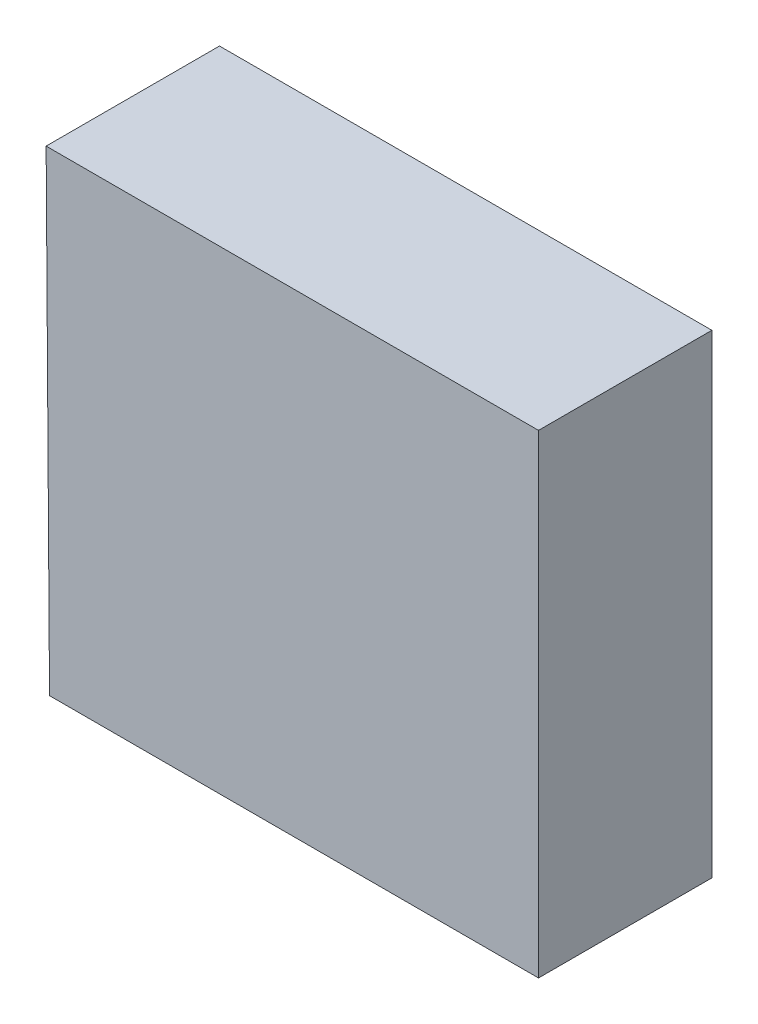
SolidWorks part; units mm, degrees
ref_plane "Front Plane" through (0, 0, 0) normal (0, 0, 1) x (1, 0, 0)
ref_plane "Top Plane" through (0, 0, 0) normal (0, 1, 0) x (1, 0, 0)
ref_plane "Right Plane" through (0, 0, 0) normal (1, 0, 0) x (0, 0, -1)
sketch "Sketch1" plane through (0, 0, 0) normal (0, 0, 1) x (1, 0, 0)
  line L0 (8.1788, 5.3086) -> (8.1788, -5.334)
  line L1 (8.1788, -5.334) -> (-2.794, -5.334)
  line L2 (-2.794, -5.334) -> (-2.8702, 5.3086)
  line L3 (-2.8702, 5.3086) -> (8.1788, 5.3086)
extrude "Component_Outline" add sketch "Sketch1" along normal blind 3.89 separate body
sketch3d "3DSketch1"
  line L0 (0, 0, 0) -> (1, 0, 0)
  line L1 (0, 0, 0) -> (0, 1, 0)
  line L2 (0, 0, 0) -> (0, 0, 1)
  point P0 (0, 0, 0)
